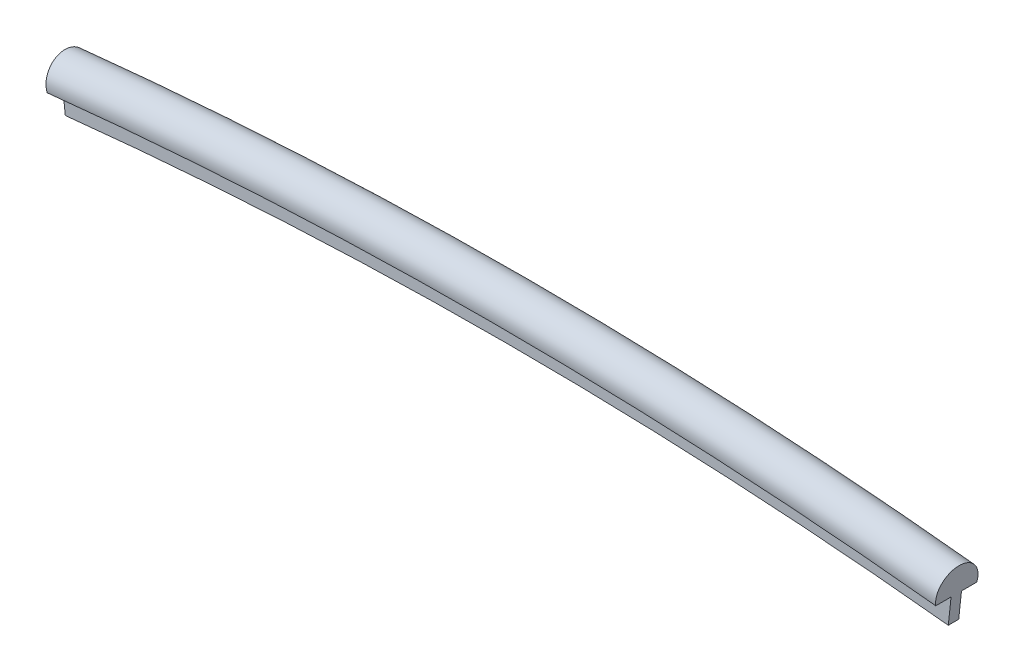
SolidWorks part; units mm, degrees
ref_plane "Front Plane" through (0, 0, 0) normal (0, 0, 1) x (1, 0, 0)
ref_plane "Top Plane" through (0, 0, 0) normal (0, 1, 0) x (1, 0, 0)
ref_plane "Right Plane" through (0, 0, 0) normal (1, 0, 0) x (0, 0, -1)
sketch "Sketch2" plane through (0, 0, 0) normal (1, 0, 0) x (0, 0, -1)
  line L0 (0, 241.3) -> (0, 0) construction
  line L2 (0, 241.3) -> (0, 239.8) construction
  line L3 (0, 239.8) -> (0.3, 239.8)
  line L4 (0, 239.8) -> (-0.3, 239.8)
  line L5 (-0.3, 239.8) -> (-0.3, 241.3)
  line L6 (0.3, 239.8) -> (0.3, 241.3)
  line L7 (0, 241.3) -> (0, 242.8) construction
  line L8 (-1.18, 241.3) -> (-0.3, 241.3)
  line L9 (0.3, 241.3) -> (1.18, 241.3)
  arc A0 (-1.18, 241.3) -> (1.18, 241.3) centre (0, 241.586) cw
  point P14 (0, 241.3)
ref_axis "Axis2" through (0, 0, 70.5976) along (0, 0, -1)
revolve "Revolve1" add sketch "Sketch2" angle 6.083 about axis through (0, 0, 70.5976) along (0, 0, -1)
